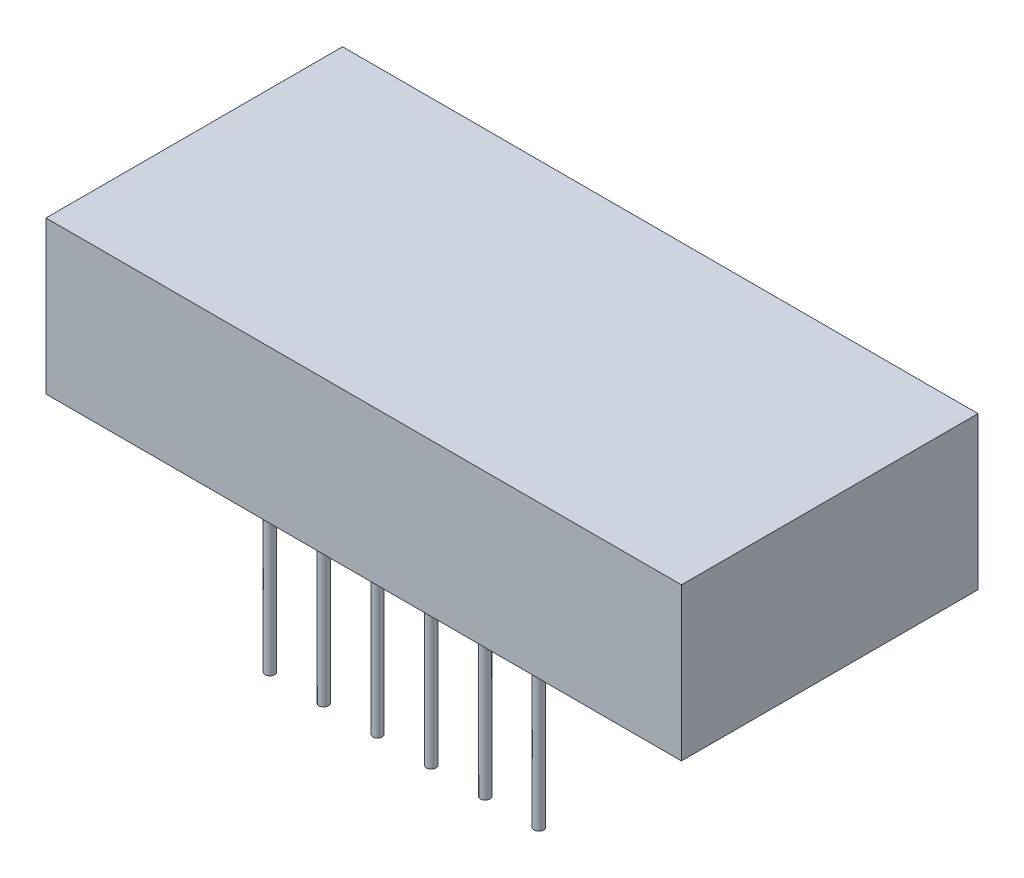
SolidWorks part; units mm, degrees
ref_plane "Front Plane" through (0, 0, 0) normal (0, 0, 1) x (1, 0, 0)
ref_plane "Top Plane" through (0, 0, 0) normal (0, 1, 0) x (1, 0, 0)
ref_plane "Right Plane" through (0, 0, 0) normal (1, 0, 0) x (0, 0, -1)
sketch "Sketch1" plane through (0, 0, 0) normal (0, 1, 0) x (1, 0, 0)
  line L1 (15, 7) -> (-15, 7)
  line L2 (15, 7) -> (15, -7)
  line L3 (15, -7) -> (-15, -7)
  line L4 (-15, 7) -> (-15, -7)
  line L5 (15, 7) -> (-15, -7) construction
  line L6 (15, -7) -> (-15, 7) construction
  point P0 (0, 0)
  dimension "D1" = 30
  dimension "D2" = 14
extrude "Boss-Extrude1" add sketch "Sketch1" along normal blind 7.2 contours L3 L4 L1 L2
sketch "Sketch2" plane through (0, 0, 0) normal (0, -1, 0) x (1, 0, 0)
  line L0 (-15, 5.08) -> (-15, -5.08) construction
  line L1 (-15, -7) -> (-15, 7) construction
  line L2 (-6.35, -7) -> (6.35, -7) construction
  line L3 (15, -7) -> (-15, -7) construction
  circle A0 centre (-6.35, -5.08) radius 0.225
  circle A1 centre (-3.81, -5.08) radius 0.225
  circle A2 centre (-1.27, -5.08) radius 0.225
  circle A3 centre (1.27, -5.08) radius 0.225
  circle A4 centre (3.81, -5.08) radius 0.225
  circle A5 centre (6.35, -5.08) radius 0.225
  circle A6 centre (-3.81, 5.08) radius 0.225
  circle A7 centre (-1.27, 5.08) radius 0.225
  circle A8 centre (1.27, 5.08) radius 0.225
  circle A9 centre (3.81, 5.08) radius 0.225
  circle A10 centre (6.35, 5.08) radius 0.225
  circle A11 centre (-6.35, 5.08) radius 0.225
  point P4 (-15, 0)
  point P11 (0, -7)
  dimension "D3" = 0.45
  dimension "D1" = 10.16
  dimension "D2" = 12.7
  dimension "D4" = 6
  dimension "D5" = 2
extrude "Boss-Extrude2" add sketch "Sketch2" along normal blind 8
